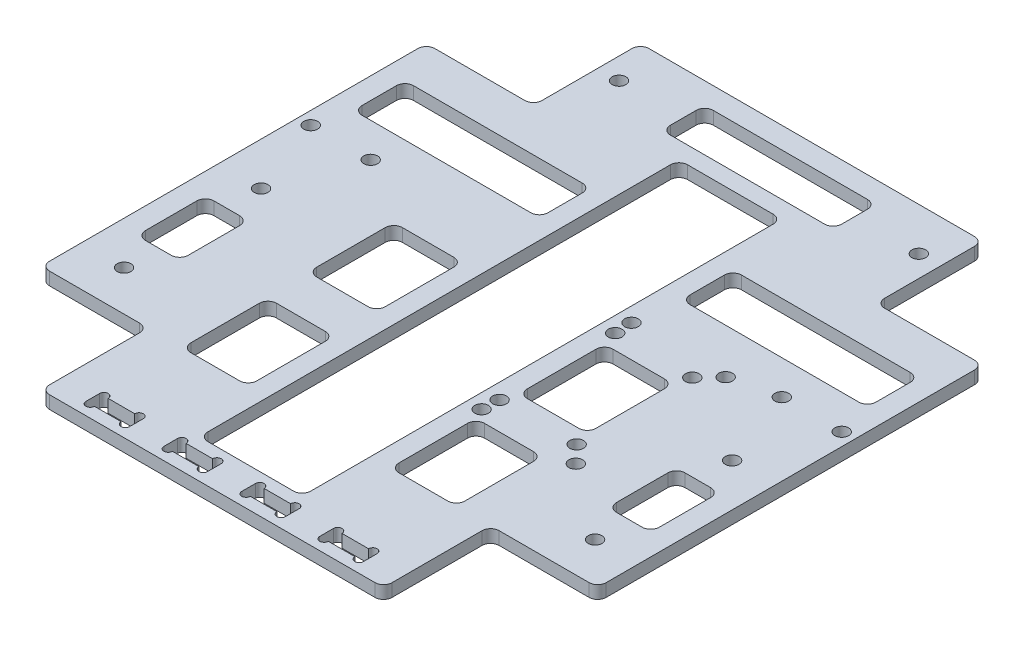
SolidWorks part; units mm, degrees
material "碳管"
ref_plane "前视基准面" through (0, 0, 0) normal (0, 0, 1) x (1, 0, 0)
ref_plane "上视基准面" through (0, 0, 0) normal (0, 1, 0) x (1, 0, 0)
ref_plane "右视基准面" through (0, 0, 0) normal (1, 0, 0) x (0, 0, -1)
sketch "草图1" plane through (0, 0, 0) normal (0, 1, 0) x (1, 0, 0)
  line L0 (-38.1882, 65) -> (165.5779, 65) construction
  line L1 (130, 140) -> (0, 140)
  line L2 (130, 140) -> (130, 0)
  line L3 (130, 0) -> (0, 0)
  line L4 (0, 140) -> (0, 0)
  line L5 (130, 140) -> (0, 0) construction
  line L6 (130, 0) -> (0, 140) construction
  line L7 (89.6, 150.1912) -> (89.6, -4.4869) construction
  line L8 (65, 150.1912) -> (65, -0.9076) construction
  line L9 (120, 140) -> (120, 0) construction
  line L10 (-19.2401, 130) -> (138.4767, 130) construction
  line L11 (53, 121) -> (77, 121)
  line L12 (53, 121) -> (53, 9)
  line L13 (53, 9) -> (77, 9)
  line L14 (77, 121) -> (77, 9)
  line L15 (53, 121) -> (77, 9) construction
  line L16 (53, 9) -> (77, 121) construction
  circle A0 centre (98.6, 78.5) radius 1.6
  circle A1 centre (80.6, 78.5) radius 1.6
  circle A2 centre (98.6, 51.5) radius 1.6
  circle A3 centre (80.6, 51.5) radius 1.6
  circle A4 centre (127, 85) radius 1.6
  circle A5 centre (113, 85) radius 1.6
  circle A6 centre (120, 66.4) radius 1.6
  circle A7 centre (120, 34.4) radius 1.6
  circle A8 centre (10, 34.4) radius 1.6
  circle A9 centre (10, 66.4) radius 1.6
  circle A10 centre (3, 85) radius 1.6
  circle A11 centre (17, 85) radius 1.6
  circle A12 centre (30, 130) radius 1.6
  circle A13 centre (100, 130) radius 1.6
  circle A14 centre (80.4, 82.5) radius 1.6
  circle A15 centre (80.4, 47.5) radius 1.6
  circle A16 centre (102.4, 82.5) radius 1.6
  circle A17 centre (102.4, 47.5) radius 1.6
  point P0 (65, 70)
  point P6 (65, 65)
  point P57 (0, 0)
  point P58 (0, 0)
  dimension "D5" = 3.2
  dimension "D9" = 14
  dimension "D10" = 3.2
  dimension "D12" = 73.6
  dimension "D13" = 32
  dimension "D17" = 3.2
  dimension "D19" = 22
  dimension "D1" = 130
  dimension "D2" = 140
  dimension "D3" = 75
  dimension "D4" = 15.6
  dimension "D6" = 18
  dimension "D7" = 27
  dimension "D8" = 10
  dimension "D11" = 55
  dimension "D14" = 24
  dimension "D15" = 9
  dimension "D16" = 10
  dimension "D18" = 70
  dimension "D20" = 35
  dimension "D21" = 15.4
extrude "凸台-拉伸1" add sketch "草图1" along normal blind 3
sketch "草图2" plane through (0, 3, 0) normal (0, 1, 0) x (1, 0, 0)
  line L0 (65, 140) -> (65, 0) construction
  line L1 (0, 140) -> (25, 140)
  line L2 (0, 140) -> (0, 115)
  line L3 (0, 115) -> (25, 115)
  line L4 (25, 140) -> (25, 115)
  line L5 (0, 0) -> (25, 0)
  line L6 (0, 0) -> (0, 25)
  line L7 (0, 25) -> (25, 25)
  line L8 (25, 0) -> (25, 25)
  line L9 (130, 140) -> (0, 140) construction
  line L10 (0, 0) -> (130, 0) construction
  line L11 (130, 25) -> (105, 25)
  line L12 (105, 0) -> (105, 25)
  line L13 (130, 0) -> (105, 0)
  line L14 (130, 0) -> (130, 25)
  line L15 (130, 115) -> (105, 115)
  line L16 (105, 140) -> (105, 115)
  line L17 (130, 140) -> (105, 140)
  line L18 (130, 140) -> (130, 115)
  line L19 (53, 65) -> (77, 65) construction
  line L20 (53, 121) -> (53, 9) construction
  line L21 (77, 9) -> (77, 121) construction
  line L22 (50.8, 6.1) -> (50.8, 2.9)
  line L23 (32.6, 6.1) -> (42.8, 6.1)
  line L24 (32.6, 6.1) -> (32.6, 2.9)
  line L25 (32.6, 2.9) -> (42.8, 2.9)
  line L26 (42.8, 6.1) -> (42.8, 2.9)
  line L27 (32.6, 6.1) -> (42.8, 2.9) construction
  line L28 (32.6, 2.9) -> (42.8, 6.1) construction
  line L29 (50.8, 6.1) -> (61, 6.1)
  line L30 (61, 6.1) -> (61, 2.9)
  line L31 (50.8, 2.9) -> (61, 2.9)
  line L32 (69, 6.1) -> (69, 2.9)
  line L33 (69, 6.1) -> (79.2, 6.1)
  line L34 (79.2, 6.1) -> (79.2, 2.9)
  line L35 (69, 2.9) -> (79.2, 2.9)
  line L36 (87.2, 6.1) -> (87.2, 2.9)
  line L37 (87.2, 6.1) -> (97.4, 6.1)
  line L38 (97.4, 6.1) -> (97.4, 2.9)
  line L39 (87.2, 2.9) -> (97.4, 2.9)
  circle A1 centre (33.6, 6.1) radius 1
  circle A2 centre (33.6, 2.9) radius 1
  circle A3 centre (41.8, 6.1) radius 1
  circle A4 centre (41.8, 2.9) radius 1
  circle A5 centre (51.8, 6.1) radius 1
  circle A6 centre (60, 6.1) radius 1
  circle A7 centre (60, 2.9) radius 1
  circle A8 centre (51.8, 2.9) radius 1
  circle A9 centre (70, 6.1) radius 1
  circle A10 centre (78.2, 6.1) radius 1
  circle A11 centre (78.2, 2.9) radius 1
  circle A12 centre (70, 2.9) radius 1
  circle A13 centre (88.2, 6.1) radius 1
  circle A14 centre (96.4, 6.1) radius 1
  circle A15 centre (96.4, 2.9) radius 1
  circle A16 centre (88.2, 2.9) radius 1
  point P24 (37.7, 4.5)
  line M17 (0, 140) -> (0, 0)
  line M18 (0, 0) -> (130, 0)
  line M19 (130, 0) -> (130, 140)
  line M20 (130, 140) -> (0, 140)
  dimension "D4" = 2
  dimension "D1" = 80
  dimension "D2" = 25
  dimension "D3" = 25
  dimension "D5" = 3.2
  dimension "D6" = 10.2
  dimension "D7" = 4.5
  dimension "D9" = 8
  dimension "D8" = 4
extrude "切除-拉伸1" cut sketch "草图2" against normal blind 3 contours L4 L3 M20 M17 | L16 L15 M20 M19 | L12 L11 M18 M19 | L8 L7 M18 M17 | A4 L26 A3 L23 A1 L24 A2 L25
sketch "草图3" plane through (0, 3, 0) normal (0, 1, 0) x (1, 0, 0)
  line L0 (65, 140) -> (65, 0) construction
  line L1 (105, 140) -> (25, 140) construction
  line L2 (25, 0) -> (105, 0) construction
  line L3 (30, 130) -> (100, 130) construction
  line L4 (53, 65) -> (77, 65) construction
  line L5 (45, 135) -> (85, 135)
  line L6 (45, 135) -> (45, 125)
  line L7 (45, 125) -> (85, 125)
  line L8 (85, 135) -> (85, 125)
  line L9 (45, 135) -> (85, 125) construction
  line L10 (45, 125) -> (85, 135) construction
  line L11 (53, 121) -> (53, 9) construction
  line L12 (77, 9) -> (77, 121) construction
  line L13 (120, 66.4) -> (120, 34.4) construction
  line L18 (80.6, 78.5) -> (98.6, 78.5) construction
  line L19 (105, 0) -> (105, 25) construction
  line L24 (130, 115) -> (105, 115) construction
  line L25 (48.4, 25) -> (33, 25)
  line L26 (81.6, 75) -> (97.6, 75)
  line L27 (81.6, 75) -> (81.6, 55)
  line L28 (81.6, 55) -> (97.6, 55)
  line L29 (97.6, 75) -> (97.6, 55)
  line L30 (81.6, 75) -> (97.6, 55) construction
  line L31 (81.6, 55) -> (97.6, 75) construction
  line L32 (81.6, 105) -> (125, 105)
  line L33 (81.6, 105) -> (81.6, 93)
  line L34 (81.6, 93) -> (125, 93)
  line L35 (125, 105) -> (125, 93)
  line L36 (81.6, 105) -> (125, 93) construction
  line L37 (81.6, 93) -> (125, 105) construction
  line L38 (81.6, 45) -> (97, 45)
  line L39 (81.6, 45) -> (81.6, 25)
  line L40 (81.6, 25) -> (97, 25)
  line L41 (97, 45) -> (97, 25)
  line L42 (81.6, 45) -> (97, 25) construction
  line L43 (81.6, 25) -> (97, 45) construction
  line L44 (33, 45) -> (33, 25)
  line L45 (115, 58.4) -> (125, 58.4)
  line L46 (115, 58.4) -> (115, 42.4)
  line L47 (115, 42.4) -> (125, 42.4)
  line L48 (125, 58.4) -> (125, 42.4)
  line L49 (115, 58.4) -> (125, 42.4) construction
  line L50 (115, 42.4) -> (125, 58.4) construction
  line L51 (48.4, 45) -> (33, 45)
  line L52 (48.4, 45) -> (48.4, 25)
  line L53 (15, 42.4) -> (5, 42.4)
  line L54 (5, 58.4) -> (5, 42.4)
  line L55 (15, 58.4) -> (5, 58.4)
  line L56 (15, 58.4) -> (15, 42.4)
  line L57 (48.4, 55) -> (32.4, 55)
  line L58 (32.4, 75) -> (32.4, 55)
  line L59 (48.4, 75) -> (32.4, 75)
  line L60 (48.4, 75) -> (48.4, 55)
  line L61 (48.4, 93) -> (5, 93)
  line L62 (5, 105) -> (5, 93)
  line L63 (48.4, 105) -> (5, 105)
  line L64 (48.4, 105) -> (48.4, 93)
  point P10 (65, 130)
  point P21 (89.6, 78.5)
  point P31 (89.6, 65)
  point P36 (103.3, 99)
  point P43 (89.3, 35)
  point P48 (120, 50.4)
  dimension "D1" = 10
  dimension "D2" = 40
  dimension "D3" = 20
  dimension "D4" = 16
  dimension "D5" = 8
  dimension "D6" = 10
  dimension "D7" = 20
  dimension "D8" = 10
  dimension "D9" = 16
  dimension "D10" = 10
  dimension "D11" = 12
extrude "切除-拉伸2" cut sketch "草图3" against normal through all
fillet "圆角1" radius 2 52 edges at (85, 1.5, -125) (45, 1.5, -125) (85, 1.5, -135) (45, 1.5, -135) (125, 1.5, -93) (81.6, 1.5, -93) (125, 1.5, -105) (81.6, 1.5, -105) (125, 1.5, -42.4) (115, 1.5, -42.4) (125, 1.5, -58.4) (115, 1.5, -58.4) (97.6, 1.5, -55) (81.6, 1.5, -55) (97.6, 1.5, -75) (81.6, 1.5, -75) (97, 1.5, -25) (81.6, 1.5, -25) (97, 1.5, -45) (81.6, 1.5, -45) (48.4, 1.5, -25) (33, 1.5, -25) (48.4, 1.5, -45) (33, 1.5, -45) (48.4, 1.5, -55) (32.4, 1.5, -55) (48.4, 1.5, -75) (32.4, 1.5, -75) (48.4, 1.5, -93) (5, 1.5, -93) (48.4, 1.5, -105) (5, 1.5, -105) (15, 1.5, -42.4) (5, 1.5, -42.4) (15, 1.5, -58.4) (5, 1.5, -58.4) (25, 1.5, 0) (105, 1.5, 0) (105, 1.5, -25) (130, 1.5, -25) (130, 1.5, -115) (105, 1.5, -115) (105, 1.5, -140) (25, 1.5, -140) (25, 1.5, -115) (0, 1.5, -115) (25, 1.5, -25) (0, 1.5, -25) (77, 1.5, -121) (53, 1.5, -9) (77, 1.5, -9) (53, 1.5, -121)
